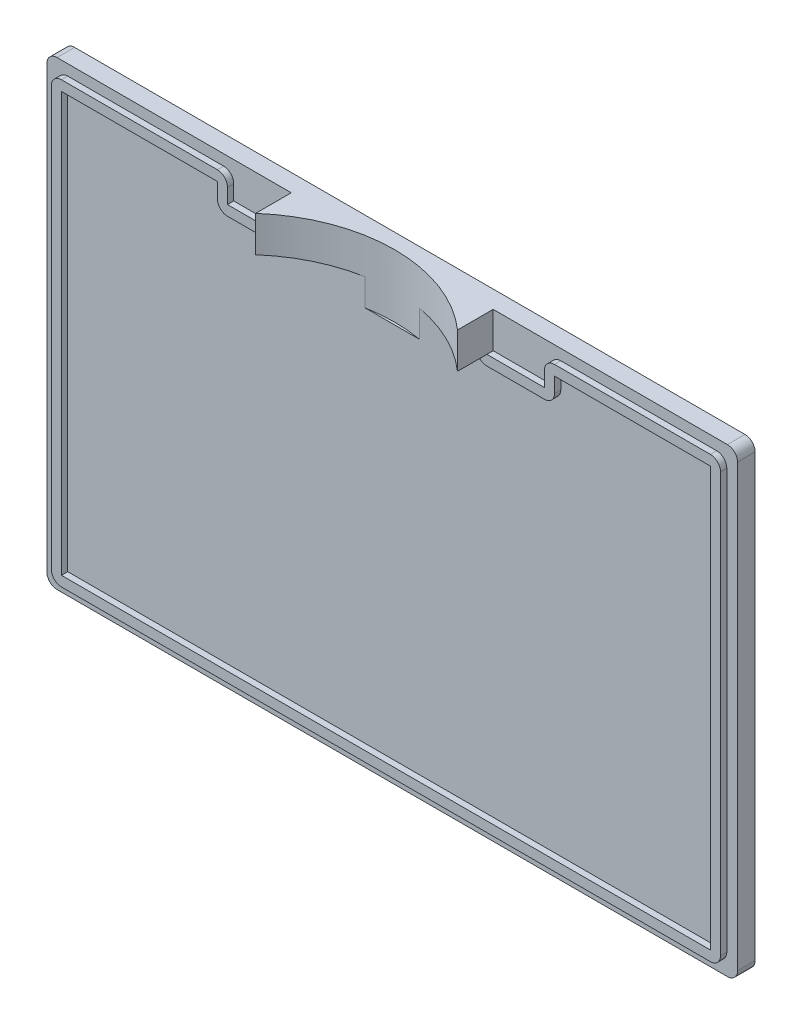
SolidWorks part; units mm, degrees
ref_plane "Front Plane" through (0, 0, 0) normal (0, 0, 1) x (1, 0, 0)
ref_plane "Top Plane" through (0, 0, 0) normal (0, 1, 0) x (1, 0, 0)
ref_plane "Right Plane" through (0, 0, 0) normal (1, 0, 0) x (0, 0, -1)
sketch "Sketch1" plane through (0, 0, 0) normal (0, 0, 1) x (1, 0, 0)
  line L0 (-53.39, 36.695) -> (53.39, 36.695)
  line L1 (-53.39, -36.695) -> (53.39, -36.695)
  line L2 (55, -35.085) -> (55, 35.085)
  line L3 (-55, -35.085) -> (-55, 35.085)
  arc A0 (55, 35.085) -> (53.39, 36.695) centre (53.39, 35.085) ccw
  arc A1 (53.39, -36.695) -> (55, -35.085) centre (53.39, -35.085) ccw
  arc A2 (-55, -35.085) -> (-53.39, -36.695) centre (-53.39, -35.085) ccw
  arc A3 (-53.39, 36.695) -> (-55, 35.085) centre (-53.39, 35.085) ccw
extrude "Boss-Extrude1" add sketch "Sketch1" along normal blind 2.8
sketch "Sketch2" plane through (0, 0, 2.8) normal (0, 0, 1) x (1, 0, 0)
  line L16 (25.2417, 33.375) -> (25.2417, 30.985)
  line L19 (-25.2417, 33.375) -> (-25.2417, 30.985)
  line L23 (-25.2417, 30.985) -> (-14.4717, 30.985)
  line L24 (14.4717, 30.985) -> (25.2417, 30.985)
  line L27 (53.29, -33.375) -> (53.29, 33.375)
  line L28 (51.68, 34.985) -> (26.8517, 34.985)
  line L29 (-51.68, 33.375) -> (-26.8517, 33.375)
  line L31 (-26.8517, 33.375) -> (-26.8517, 30.985)
  line L32 (-26.8517, 34.985) -> (-51.68, 34.985)
  line L33 (-53.29, 33.375) -> (-53.29, -33.375)
  line L34 (-51.68, -34.985) -> (51.68, -34.985)
  line L35 (-25.2417, 29.375) -> (-16.0817, 29.375)
  line L39 (16.0817, 29.375) -> (25.2417, 29.375)
  line L40 (26.8517, 30.985) -> (26.8517, 33.375)
  line L41 (26.8517, 33.375) -> (51.68, 33.375)
  line L42 (51.68, 33.375) -> (51.68, -33.375)
  line L43 (51.68, -33.375) -> (-51.68, -33.375)
  line L44 (-51.68, -33.375) -> (-51.68, 33.375)
  arc A0 (-51.68, -34.985) -> (-53.29, -33.375) centre (-51.68, -33.375) cw
  arc A1 (51.68, -34.985) -> (53.29, -33.375) centre (51.68, -33.375) ccw
  arc A2 (51.68, 34.985) -> (53.29, 33.375) centre (51.68, 33.375) cw
  arc A4 (25.2417, 29.375) -> (26.8517, 30.985) centre (25.2417, 30.985) ccw
  arc A5 (26.8517, 34.985) -> (25.2417, 33.375) centre (26.8517, 33.375) ccw
  arc A7 (-53.29, 33.375) -> (-51.68, 34.985) centre (-51.68, 33.375) cw
  arc A8 (-26.8517, 30.985) -> (-25.2417, 29.375) centre (-25.2417, 30.985) ccw
  arc A11 (-25.2417, 33.375) -> (-26.8517, 34.985) centre (-26.8517, 33.375) ccw
  arc A13 (-16.0817, 29.375) -> (-14.4717, 30.985) centre (-16.0817, 30.985) ccw
  arc A14 (14.4717, 30.985) -> (16.0817, 29.375) centre (16.0817, 30.985) ccw
extrude "Boss-Extrude2" add sketch "Sketch2" along normal blind 1
sketch "Sketch3" plane through (0, 0, 2.8) normal (0, 0, 1) x (1, 0, 0)
  line L1 (-16.0817, 30.985) -> (16.0817, 30.985)
  line L2 (-16.0817, 30.985) -> (-16.0817, 36.695)
  line L3 (-16.0817, 36.695) -> (16.0817, 36.695)
  line L4 (16.0817, 30.985) -> (16.0817, 36.695)
extrude "Boss-Extrude3" add sketch "Sketch3" along normal blind 5.8
sketch "Sketch4" plane through (0, 36.695, 0) normal (0, 1, 0) x (1, 0, 0)
  line L6 (-16.0817, -8.4794) -> (-16.0817, -8.6)
  line L7 (-16.0817, -8.6) -> (16.0817, -8.6)
  line L8 (16.0817, -8.4794) -> (16.0817, -8.6)
  arc A1 (16.0817, -8.4794) -> (-16.0817, -8.4794) centre (0, -26.75) ccw
extrude "Cut-Extrude1" cut sketch "Sketch4" against normal blind 10
